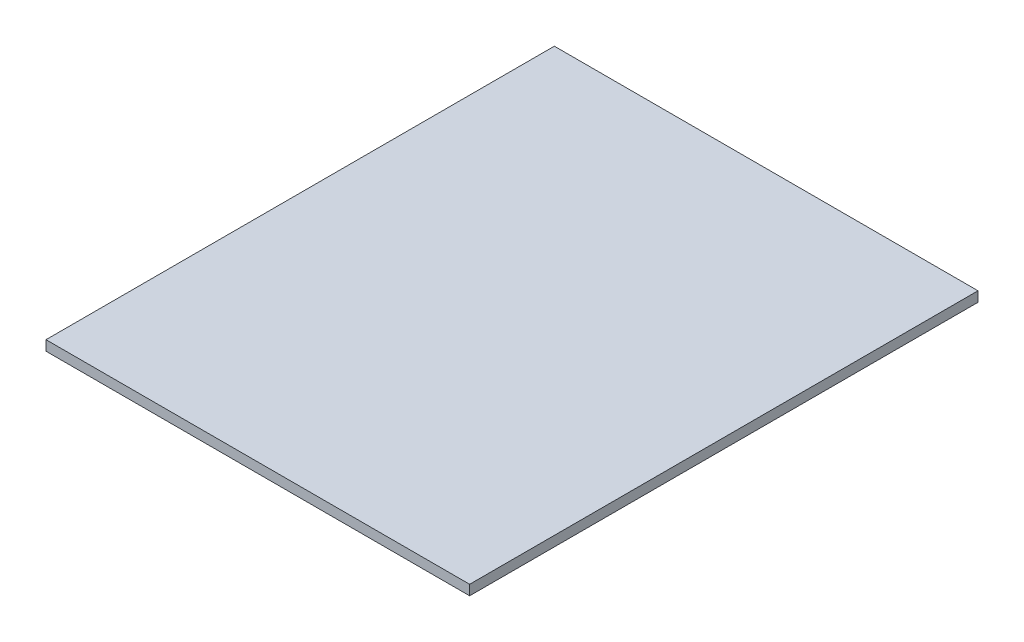
SolidWorks part; units mm, degrees
ref_plane "Front Plane" through (0, 0, 0) normal (0, 0, 1) x (1, 0, 0)
ref_plane "Top Plane" through (0, 0, 0) normal (0, 1, 0) x (1, 0, 0)
ref_plane "Right Plane" through (0, 0, 0) normal (1, 0, 0) x (0, 0, -1)
sketch "Sketch1" plane through (0, 0, 0) normal (0, 1, 0) x (1, 0, 0)
  line L1 (-63.5, 76.2) -> (63.5, 76.2)
  line L2 (-63.5, 76.2) -> (-63.5, -76.2)
  line L3 (-63.5, -76.2) -> (63.5, -76.2)
  line L4 (63.5, 76.2) -> (63.5, -76.2)
  line L5 (-63.5, 76.2) -> (63.5, -76.2) construction
  line L6 (-63.5, -76.2) -> (63.5, 76.2) construction
  point P0 (0, 0)
  dimension "D1" = 152.4
  dimension "D2" = 127
extrude "Boss-Extrude1" add sketch "Sketch1" along normal blind 3
